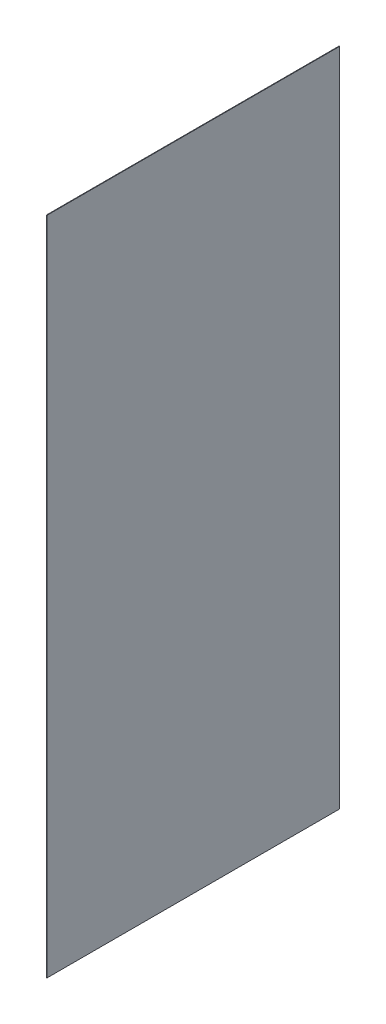
SolidWorks part; units mm, degrees
ref_plane "Front Plane" through (0, 0, 0) normal (0, 0, 1) x (1, 0, 0)
ref_plane "Top Plane" through (0, 0, 0) normal (0, 1, 0) x (1, 0, 0)
ref_plane "Right Plane" through (0, 0, 0) normal (1, 0, 0) x (0, 0, -1)
other "Configuration Table"
sketch "Sketch1" plane through (0, 0, 0) normal (0, 0, 1) x (1, 0, 0)
  line L1 (0, 120) -> (1.5, 120)
  line L2 (0, 120) -> (0, 1970)
  line L3 (0, 1970) -> (1.5, 1970)
  line L4 (1.5, 120) -> (1.5, 1970)
extrude "OVEN_dis_yan_sol_1" add sketch "Sketch1" against normal blind 820 separate body
